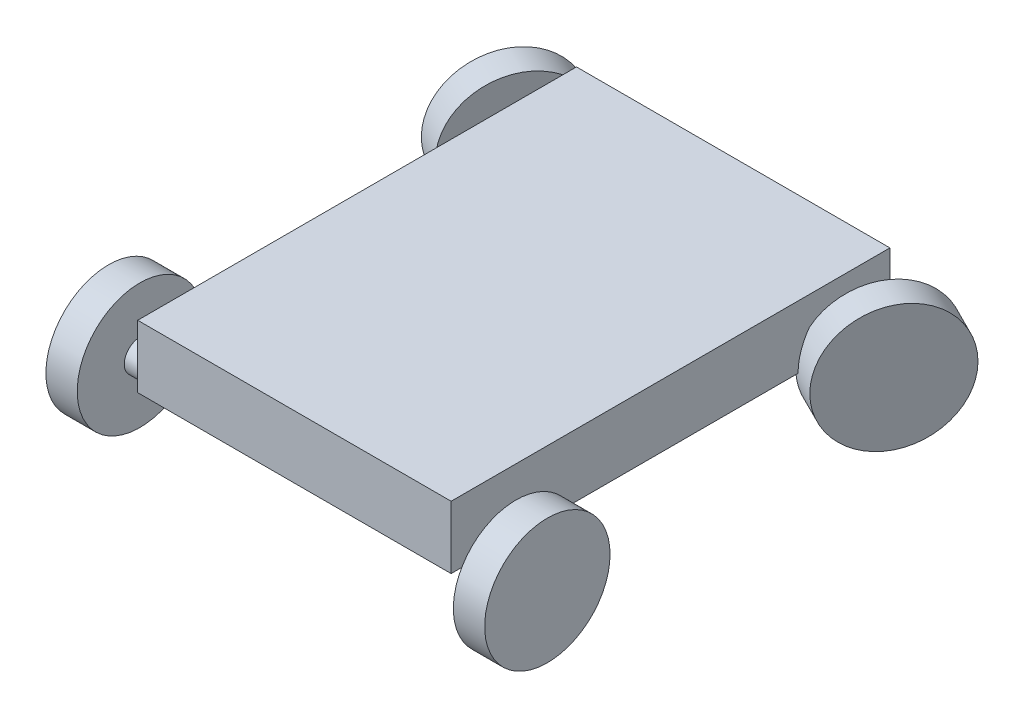
SolidWorks part; units mm, degrees
ref_plane "Alzado" through (0, 0, 0) normal (0, 0, 1) x (1, 0, 0)
ref_plane "Planta" through (0, 0, 0) normal (0, 1, 0) x (1, 0, 0)
ref_plane "Vista lateral" through (0, 0, 0) normal (1, 0, 0) x (0, 0, -1)
sketch "Croquis2" plane through (0, 0, 0) normal (0, 1, 0) x (1, 0, 0)
  line L1 (-25, -35) -> (25, -35)
  line L2 (-25, -35) -> (-25, 35)
  line L3 (-25, 35) -> (25, 35)
  line L4 (25, -35) -> (25, 35)
  line L5 (-25, -35) -> (25, 35) construction
  line L6 (-25, 35) -> (25, -35) construction
  point P0 (0, 0)
  dimension "D1" = 50
  dimension "D2" = 70
extrude "Saliente-Extruir1" add sketch "Croquis2" along normal blind 10
sketch "Croquis4" plane through (0, 0, 0) normal (1, 0, 0) x (0, 0, -1)
  line L0 (27.5, 0) -> (-27.5, 0) construction
  circle A0 centre (-29.6468, 0) radius 2.5
  dimension "D1" = 5
extrude "Saliente-Extruir2" add sketch "Croquis4" along normal blind 30 and the other way blind 30
sketch "Croquis5" plane through (30, 0, 0) normal (1, 0, 0) x (0, 0, -1)
  circle A0 centre (-29.6468, 0) radius 10
  dimension "D1" = 20
extrude "Saliente-Extruir3" add sketch "Croquis5" along normal blind 5
mirror "Simetría1" about plane through (0, 0, 0) normal (1, 0, 0) of "Saliente-Extruir3"
mirror "Simetría2" about plane through (0, 0, 0) normal (0, 0, 1) of "Saliente-Extruir2"
sketch "Croquis7" plane through (0, 0, 0) normal (0, 1, 0) x (1, 0, 0)
  line L0 (-30, 27.1468) -> (-27.5, 32.1468)
  line L1 (-30, 32.1468) -> (-30, 27.1468) construction
  line L2 (-25, 32.1468) -> (-30, 32.1468) construction
  line L3 (-27.5, 32.1468) -> (-30, 32.1468)
  line L4 (-30, 32.1468) -> (-30, 27.1468)
  line L5 (30, 32.1468) -> (27.5, 27.1468)
  line L6 (25, 27.1468) -> (30, 27.1468) construction
  line L7 (27.5, 27.1468) -> (30, 27.1468)
  line L8 (30, 27.1468) -> (30, 32.1468) construction
  line L9 (30, 27.1468) -> (30, 32.1468)
extrude "Cortar-Extruir1" cut sketch "Croquis7" against normal blind 5 and the other way blind 5 contours L4 L0 L3 | L9 L5 L7
sketch "Croquis8" plane through (11.1413, 0, 5.5706) normal (0.8944, 0, 0.4472) x (0.4472, 0, -0.8944)
  line L0 (38.5, 0) -> (-38.5, 0) construction
  circle A0 centre (39.3743, 0) radius 10
  dimension "D1" = 20
extrude "Saliente-Extruir4" add sketch "Croquis8" along normal blind 5
sketch "Croquis9" plane through (-34.8587, 0, -17.4294) normal (-0.8944, 0, -0.4472) x (-0.4472, 0, 0.8944)
  line L0 (39.9818, 0) -> (-39.9818, 0) construction
  circle A0 centre (-13.6595, 0) radius 10
  dimension "D1" = 20
extrude "Saliente-Extruir5" add sketch "Croquis9" along normal blind 5
